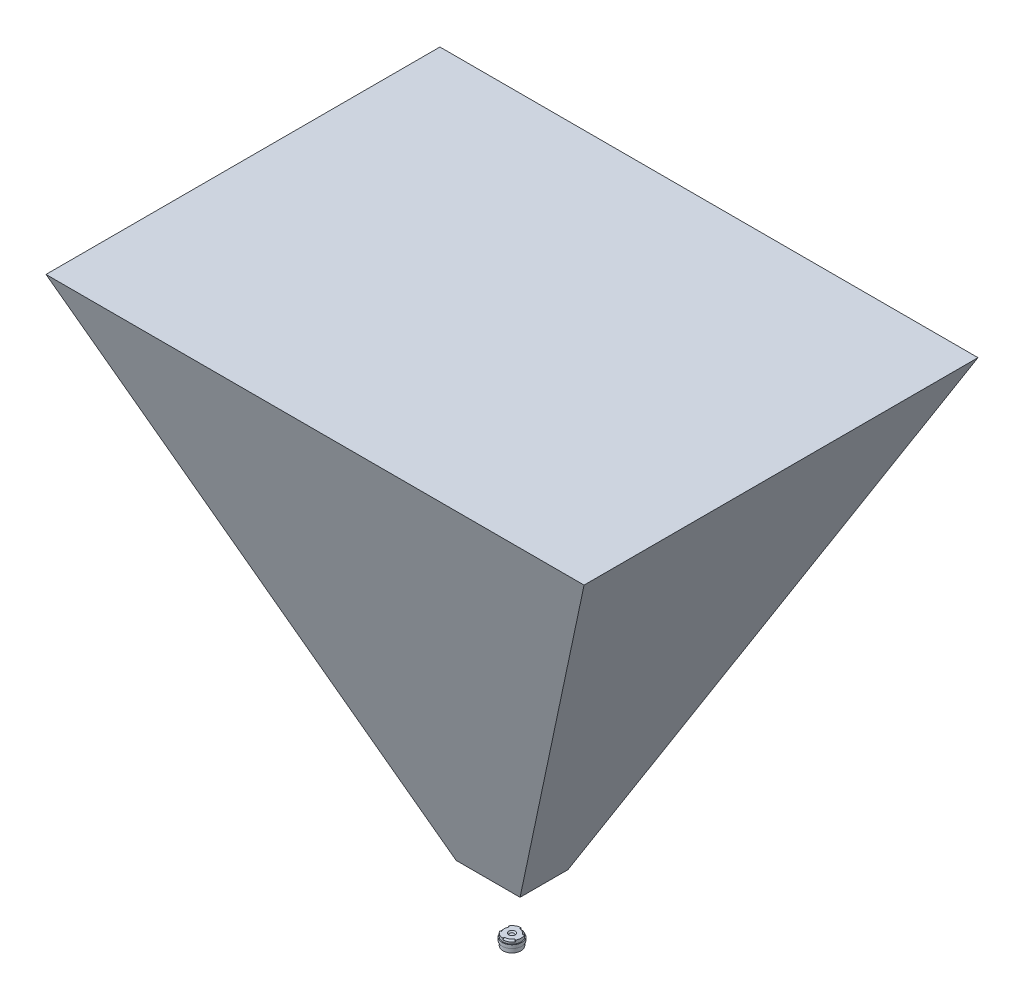
SolidWorks part; units mm, degrees
material "ABS PC"
ref_plane "Vorne" through (0, 0, 0) normal (0, 0, 1) x (1, 0, 0)
ref_plane "Oben" through (0, 0, 0) normal (0, 1, 0) x (1, 0, 0)
ref_plane "Rechts" through (0, 0, 0) normal (1, 0, 0) x (0, 0, -1)
sketch "Skizze3" plane through (0, 0, 0) normal (0, 0, 1) x (1, 0, 0)
  line L0 (0, 0) -> (0, -2.1568) construction
  line L1 (1, 0.8) -> (2.75, 0.8)
  line L2 (2.75, 0.8) -> (2.75, -2.55)
  line L3 (2.75, -2.55) -> (2.1, -2.55)
  line L4 (1, 0.8) -> (0.625, 0.425)
  line L5 (0.8125, 0.6125) -> (0.8125, 0.8) construction
  line L6 (0.8125, 0.8) -> (1, 0.8) construction
  line L7 (2.1, -2.55) -> (1.8, -2.25)
  line L8 (2.1, -2.55) -> (2.1, -2.4) construction
  line L9 (2.1, -2.4) -> (1.95, -2.4) construction
  line L10 (0, -2.55) -> (0, 0.525)
  arc A0 (1.8, -2.25) -> (0, -2.55) centre (0, 3) cw
  arc A1 (0, 0.525) -> (0.625, 0.425) centre (0, -1.4781) cw
  dimension "D6" = 0.1
  dimension "D1" = 3.35
  dimension "D2" = 5.5
  dimension "D3" = 2
  dimension "D4" = 1.25
  dimension "D5" = 3.6
  dimension "D7" = 0.8
  dimension "D8" = 0.3
revolve "Body" add sketch "Skizze3" angle 360 about L0
sketch "Skizze4" plane through (0, 0, 0) normal (0, 0, 1) x (1, 0, 0)
  line L0 (0, 0) -> (0, 1.3093) construction
  line L1 (2.75, -2.55) -> (2.75, 0.8) construction
  line L2 (2.75, -0.2) -> (3, -0.2)
  line L3 (2.75, -0.2) -> (2.75, -1.2)
  line L4 (2.75, -1.2) -> (3, -1.2)
  line L5 (3, -0.2) -> (3, -1.2)
  line L6 (2.75, 0.8) -> (-2.75, 0.8) construction
  dimension "D1" = 2
  dimension "D2" = 1
  dimension "D3" = 6
revolve "Thread" add sketch "Skizze4" angle 360 about L0
sketch "Skizze5" plane through (0, 0, 0) normal (1, 0, 0) x (0, 0, -1)
  line L0 (0, 0) -> (0, -3.7681) construction
  line L1 (2.75, 0.8) -> (2.75, 0.35)
  line L2 (2.75, -0.2) -> (2.75, 0.8) construction
  line L3 (2.75, 0.35) -> (2.3, 0.8)
  line L4 (2.75, 0.8) -> (-2.75, 0.8) construction
  line L5 (2.3, 0.8) -> (2.75, 0.8)
  dimension "D1" = 0.45
revolve "Toolface" cut sketch "Skizze5" angle 60 about L0
pattern_circular "Kreismuster1" count 3 over 360 about axis through (0, 0, 0) along (0, 1, 0) of "Toolface"
sketch "Skizze6" plane through (0, 0, 0) normal (1, 0, 0) x (0, 0, -1)
  line L0 (0, 0) -> (0, 10.2784) construction
  line L1 (-7.2794, 18.7078) -> (-60, 163.5565)
  line L2 (-60, 163.5565) -> (60, 163.5565)
  line L3 (-7.2794, 18.7078) -> (7.2794, 18.7078)
  line L4 (0, 163.5565) -> (0, 18.7078) construction
  line L5 (-7.2794, 18.7078) -> (0, -1.2922) construction
  line L8 (7.2794, 18.7078) -> (60, 163.5565)
  point P3 (-0.625, 0.425)
  dimension "D1" = 120
  dimension "D2" = 20
  dimension "D3" = 40
extrude "FOV - 3,6mm f/2,9" add sketch "Skizze6" along normal mid plane 200 separate body
sketch "Skizze8" plane through (0, 0, 0) normal (0, 0, 1) x (1, 0, 0)
  line L0 (0, 0) -> (0, 233.3089) construction
  line L1 (-9.7405, 18.7078) -> (-81.9594, 163.5565)
  line L2 (100, 18.7078) -> (-100, 18.7078) construction
  line L3 (100, 163.5565) -> (-100, 163.5565) construction
  line L4 (-81.9594, 163.5565) -> (81.9594, 163.5565)
  line L5 (-9.7405, 18.7078) -> (9.7405, 18.7078)
  line L8 (9.7405, 18.7078) -> (81.9594, 163.5565)
  circle A0 centre (0, 0) radius 5
  point P9 (-0.625, 0.425)
  point P16 (0, 18.7078)
  point P17 (0, 163.5565)
  dimension "D2" = 10
  dimension "D1" = 53
extrude "FOV2" cut sketch "Skizze8" against normal through all and the other way through all flip side to cut
